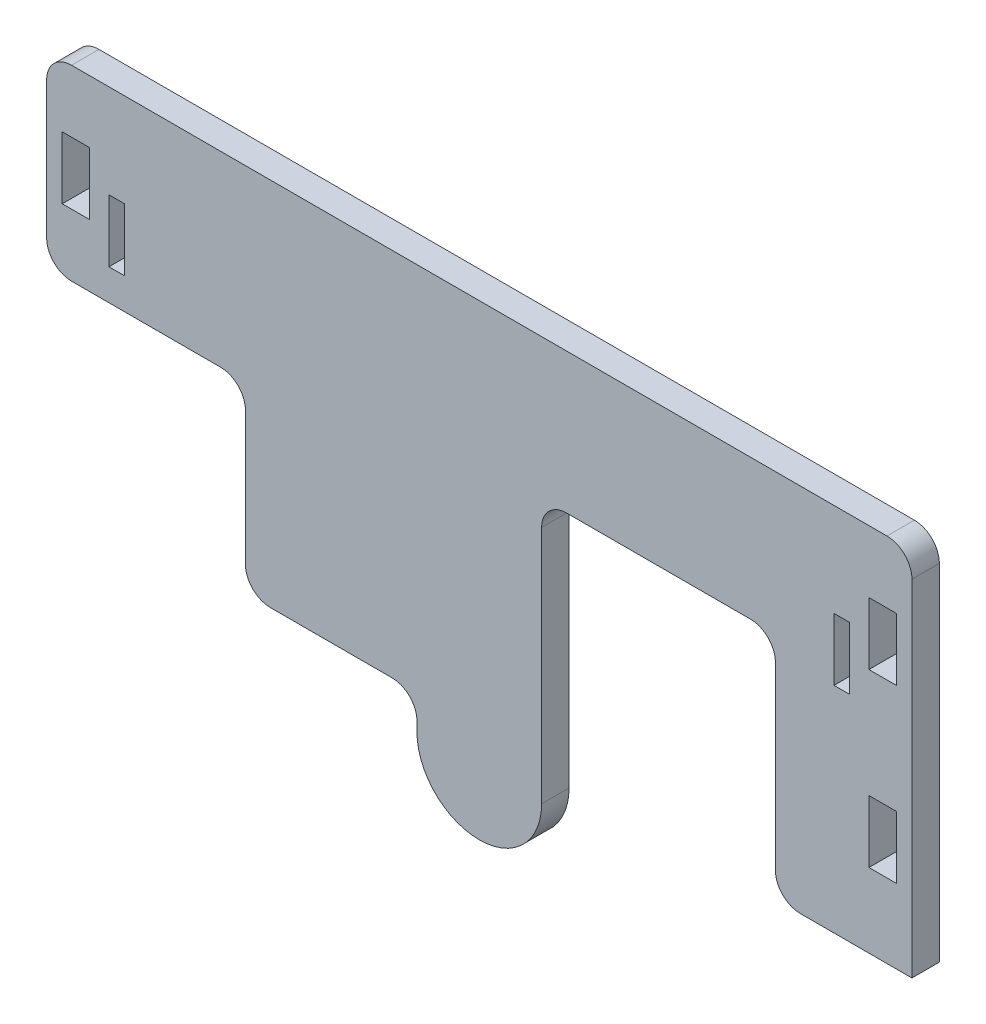
SolidWorks part; units mm, degrees
ref_plane "Front Plane" through (0, 0, 0) normal (0, 0, 1) x (1, 0, 0)
ref_plane "Top Plane" through (0, 0, 0) normal (0, 1, 0) x (1, 0, 0)
ref_plane "Right Plane" through (0, 0, 0) normal (1, 0, 0) x (0, 0, -1)
sketch "Sketch1" plane through (0, 0, 0) normal (0, 0, 1) x (1, 0, 0)
  line L0 (69.4754, -4.3815) -> (69.4754, 33.3375)
  line L1 (69.4754, 33.3375) -> (-18.6626, 33.3375)
  line L2 (-18.6626, 33.3375) -> (-18.6626, 14.2875)
  line L3 (-17.0751, 14.2875) -> (-14.2811, 14.2875) construction
  line L4 (69.4754, -4.3815) -> (55.5689, -4.3815)
  line L6 (55.5689, -4.3815) -> (55.5689, 19.05)
  line L7 (55.5689, 19.05) -> (31.7564, 19.05)
  line L8 (31.7564, 19.05) -> (31.7564, -7.8778)
  line L9 (25.4064, 33.3375) -> (25.4064, -17.5485) construction
  line L10 (65.0939, 9.525) -> (65.0939, 3.175) construction
  line L11 (50, 12.7) -> (37.3, 12.7) construction
  line L12 (-18.6626, 14.2875) -> (1.5875, 14.2875)
  line L13 (1.5875, 14.2875) -> (1.5875, -4.3815)
  line L14 (1.5875, -4.3815) -> (19.0564, -4.3815)
  line L15 (19.0564, -4.3815) -> (19.0564, -7.8778)
  line L16 (-22.0586, -14.2278) -> (72.8714, -14.2278) construction
  line L17 (0, 25.4) -> (0, 0) construction
  line L18 (-18.6626, -2.794) -> (-18.6626, 0) construction
  line L19 (69.4754, -2.794) -> (66.3004, -2.794) construction
  line L20 (69.4754, -2.794) -> (69.4754, 0) construction
  arc A0 (31.7564, -7.8778) -> (19.0564, -7.8778) centre (25.4064, -7.8778) cw
  arc A1 (-23.8239, -12.4625) -> (-20.2933, -12.4625) centre (-22.0586, -12.4625) ccw construction
  arc A2 (71.1061, -12.4625) -> (74.6367, -12.4625) centre (72.8714, -12.4625) ccw construction
  point P19 (25.4064, -14.2278)
  dimension "D1" = 6.35
  dimension "D2" = 9.525
  dimension "D3" = 6.35
  dimension "D4" = 1.5875
  dimension "D5" = 1.5875
extrude "Boss-Extrude1" add sketch "Sketch1" along normal blind 2.794 contours L1 L2 L12 L13 L14 L15 A0 L8 L7 L6 L4 L0
sketch "Sketch3" plane through (0, 0, 2.794) normal (0, 0, 1) x (1, 0, 0)
  line L0 (-14.2811, 20.6375) -> (-14.2811, 26.9875) construction
  line L1 (-14.2811, 26.9875) -> (-17.0751, 26.9875) construction
  line L2 (-17.0751, 26.9875) -> (-17.0751, 20.6375) construction
  line L3 (-17.0751, 20.6375) -> (-14.2811, 20.6375) construction
  line L4 (65.0939, 26.9875) -> (65.0939, 20.6375) construction
  line L5 (65.0939, 20.6375) -> (67.8879, 20.6375) construction
  line L6 (67.8879, 20.6375) -> (67.8879, 26.9875) construction
  line L7 (67.8879, 26.9875) -> (65.0939, 26.9875) construction
  line L8 (65.0939, 9.525) -> (65.0939, 3.175) construction
  line L9 (65.0939, 3.175) -> (67.8879, 3.175) construction
  line L10 (67.8879, 3.175) -> (67.8879, 9.525) construction
  line L11 (67.8879, 9.525) -> (65.0939, 9.525) construction
  line L12 (-14.2811, 20.6375) -> (-14.2811, 26.9875)
  line L13 (-14.2811, 26.9875) -> (-17.0751, 26.9875)
  line L14 (-17.0751, 26.9875) -> (-17.0751, 20.6375)
  line L15 (-17.0751, 20.6375) -> (-14.2811, 20.6375)
  line L16 (65.0939, 26.9875) -> (65.0939, 20.6375)
  line L17 (65.0939, 20.6375) -> (67.8879, 20.6375)
  line L18 (67.8879, 20.6375) -> (67.8879, 26.9875)
  line L19 (67.8879, 26.9875) -> (65.0939, 26.9875)
  line L20 (65.0939, 9.525) -> (65.0939, 3.175)
  line L21 (65.0939, 3.175) -> (67.8879, 3.175)
  line L22 (67.8879, 3.175) -> (67.8879, 9.525)
  line L23 (67.8879, 9.525) -> (65.0939, 9.525)
  line L24 (-14.2811, 23.8125) -> (-17.0751, 23.8125) construction
  line L25 (-10.7251, 23.8125) -> (-12.3126, 23.8125)
  line L26 (-10.7251, 23.8125) -> (-10.7251, 17.4625)
  line L27 (-10.7251, 17.4625) -> (-12.3126, 17.4625)
  line L28 (-12.3126, 23.8125) -> (-12.3126, 17.4625)
  line L29 (-14.2811, 17.4625) -> (-17.0751, 17.4625) construction
  line L30 (69.4754, -4.3815) -> (69.4754, 33.3375) construction
  line L31 (63.1254, 23.8125) -> (61.5379, 23.8125)
  line L32 (63.1254, 23.8125) -> (63.1254, 17.4625)
  line L33 (63.1254, 17.4625) -> (61.5379, 17.4625)
  line L34 (61.5379, 23.8125) -> (61.5379, 17.4625)
  line L35 (-18.6626, 33.3375) -> (-18.6626, 14.2875) construction
  dimension "D1" = 1.5875
  dimension "D2" = 6.35
  dimension "D3" = 1.5875
  dimension "D4" = 6.35
extrude "Cut-Extrude1" cut sketch "Sketch3" against normal through all
fillet "Fillet1" radius 2.54 9 edges at (1.5875, 14.2875, 1.397) (1.5875, -4.3815, 1.397) (55.5689, -4.3815, 1.397) (31.7564, 19.05, 1.397) (55.5689, 19.05, 1.397) (-18.6626, 33.3375, 1.397) (69.4754, 33.3375, 1.397) (-18.6626, 14.2875, 1.397) (19.0564, -4.3815, 1.397)
equation "\"D1@Boss-Extrude1\"=\"thick@assy.sldasm\""
